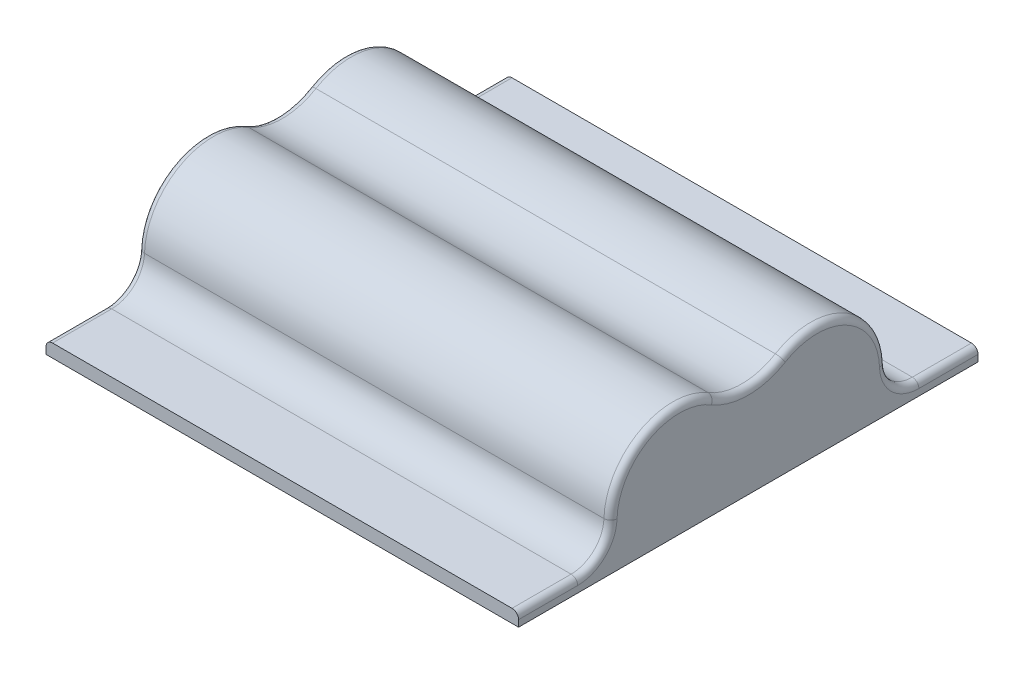
SolidWorks part; units mm, degrees
ref_plane "Alzado" through (0, 0, 0) normal (0, 0, 1) x (1, 0, 0)
ref_plane "Planta" through (0, 0, 0) normal (0, 1, 0) x (1, 0, 0)
ref_plane "Vista lateral" through (0, 0, 0) normal (1, 0, 0) x (0, 0, -1)
sketch "Sketch1" plane through (0, 0, 0) normal (0, 1, 0) x (1, 0, 0)
  line L1 (-36, -35) -> (36, -35)
  line L2 (-36, -35) -> (-36, 35)
  line L3 (-36, 35) -> (36, 35)
  line L4 (36, -35) -> (36, 35)
  point P4 (0, 35)
  point P6 (36, 0)
  dimension "D1" = 72
  dimension "D2" = 70
extrude "Boss-Extrude1" add sketch "Sketch1" along normal blind 2
sketch "Sketch2" plane through (0, 0, 0) normal (1, 0, 0) x (0, 0, -1)
  line L0 (-35, 2) -> (35, 2) construction
  line L1 (-10.5, 17) -> (10.5, 17) construction
  line L2 (-25.9919, 2) -> (-19.75, 2)
  line L3 (-19.75, 6.5) -> (-19.75, 2)
  line L4 (19.75, 6.5) -> (19.75, 2)
  line L5 (19.75, 2) -> (25.9919, 2)
  line L7 (-3.5524, 12.6068) -> (3.5524, 12.6068)
  arc A0 (-5.122, 15.5181) -> (-20.9945, 6.8387) centre (-10.5, 6.5) ccw
  arc A1 (20.9945, 6.8387) -> (5.122, 15.5181) centre (10.5, 6.5) ccw
  arc A2 (-25.9919, 2) -> (-20.9945, 6.8387) centre (-25.9919, 7) ccw
  arc A3 (20.9945, 6.8387) -> (25.9919, 2) centre (25.9919, 7) ccw
  arc A4 (-5.122, 15.5181) -> (5.122, 15.5181) centre (0, 24.1068) ccw
  arc A5 (-3.5524, 12.6068) -> (-19.75, 6.5) centre (-10.5, 6.5) ccw
  arc A6 (19.75, 6.5) -> (3.5524, 12.6068) centre (10.5, 6.5) ccw
  point P7 (0, 17)
  point P21 (0, 14.1068)
  dimension "D1" = 21
  dimension "D3" = 10
  dimension "D4" = 20
  dimension "D5" = 18.5
  dimension "D2" = 15
  dimension "D6" = 1.5
extrude "Boss-Extrude2" add sketch "Sketch2" along normal blind 34 and the other way blind 34
sketch "Sketch3" plane through (0, 0, 0) normal (1, 0, 0) x (0, 0, -1)
  line L0 (-19.75, 2) -> (-19.75, 0)
  line L1 (-35, 0) -> (35, 0) construction
  line L2 (19.75, 2) -> (19.75, 0)
  line L3 (19.75, 0) -> (-19.75, 0)
  line L4 (19.75, 2) -> (-19.75, 2)
extrude "Cut-Extrude1" cut sketch "Sketch3" against normal up to surface and the other way up to surface
sketch "Sketch4" plane through (34, 0, 0) normal (1, 0, 0) x (0, 0, -1)
  line L0 (-25.9919, 2) -> (25.9919, 2)
  arc A0 (-5.122, 15.5181) -> (-20.9945, 6.8387) centre (-10.5, 6.5) ccw
  arc A1 (20.9945, 6.8387) -> (5.122, 15.5181) centre (10.5, 6.5) ccw
  arc A2 (20.9945, 6.8387) -> (25.9919, 2) centre (25.9919, 7) ccw
  arc A3 (-5.122, 15.5181) -> (5.122, 15.5181) centre (0, 24.1068) ccw
  arc A4 (-25.9919, 2) -> (-20.9945, 6.8387) centre (-25.9919, 7) ccw
  arc A6 (-5.122, 15.5181) -> (-20.9945, 6.8387) centre (-10.5, 6.5) ccw construction
  arc A7 (20.9945, 6.8387) -> (5.122, 15.5181) centre (10.5, 6.5) ccw construction
  arc A8 (-5.122, 15.5181) -> (5.122, 15.5181) centre (0, 24.1068) ccw construction
  arc A9 (-25.9919, 2) -> (-20.9945, 6.8387) centre (-25.9919, 7) ccw construction
  arc A10 (20.9945, 6.8387) -> (25.9919, 2) centre (25.9919, 7) ccw construction
extrude "Boss-Extrude3" add sketch "Sketch4" along normal blind 2
fillet "Fillet2" radius 1 7 edges at (36, 3.4079, -22.5139) (36, 15.7126, -15.5376) (36, 14.1068, 0) (36, 3.4079, 22.5139) (36, 15.7126, 15.5376) (36, 2, -30.496) (36, 2, 30.496)
mirror "Mirror1" about plane through (0, 0, 0) normal (1, 0, 0) of "Fillet2", "Boss-Extrude3"
